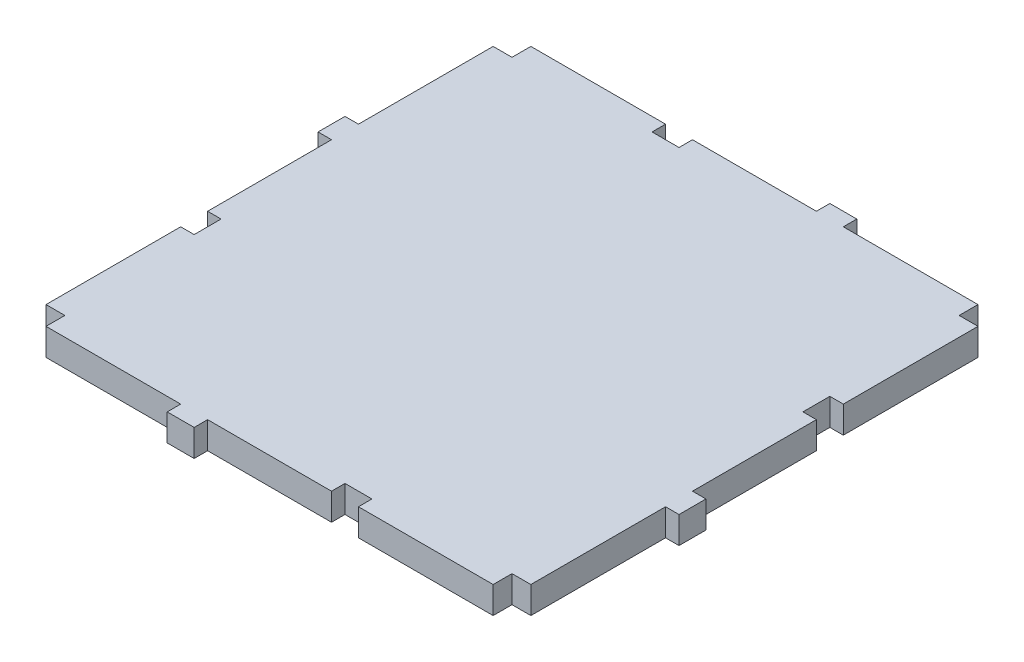
SolidWorks part; units mm, degrees
material "Pine"
ref_plane "Front Plane" through (0, 0, 0) normal (0, 0, 1) x (1, 0, 0)
ref_plane "Top Plane" through (0, 0, 0) normal (0, 1, 0) x (1, 0, 0)
ref_plane "Right Plane" through (0, 0, 0) normal (1, 0, 0) x (0, 0, -1)
sketch "Sketch2" plane through (0, 0, 0) normal (0, 1, 0) x (1, 0, 0)
  line L0 (-90, 180) -> (-90, 0)
  line L1 (0, 0) -> (-180, 0)
  line L2 (0, 0) -> (0, 180)
  line L3 (0, 180) -> (-180, 180)
  line L4 (-180, 0) -> (-180, 180)
  line L5 (-180, 90) -> (0, 90)
  dimension "D1" = 180
  dimension "D2" = 180
extrude "Boss-Extrude1" add sketch "Sketch2" along normal blind 10 contours L2 L3 L4 L1
sketch "Sketch9" plane through (0, 10, 0) normal (0, 1, 0) x (1, 0, 0)
  line L0 (-180, 0) -> (-180, 180) construction
  line L2 (0, 0) -> (-180, 0) construction
  line L3 (7, -7) -> (-7, -7)
  line L5 (0, 0) -> (0, 180) construction
  line L11 (7, -7) -> (7, 7)
  line L12 (7, 7) -> (-7, 7)
  line L13 (-7, -7) -> (-7, 7)
  line L14 (7, -7) -> (-7, 7) construction
  line L23 (7, 7) -> (-7, -7) construction
  line L24 (-187, 7) -> (-173, 7)
  line L25 (-187, 7) -> (-187, -7)
  line L26 (-187, -7) -> (-173, -7)
  line L35 (-173, 7) -> (-173, -7)
  line L36 (-187, 7) -> (-173, -7) construction
  line L37 (-187, -7) -> (-173, 7) construction
  line L47 (-173, 173) -> (-187, 173)
  line L48 (-173, 173) -> (-173, 187)
  line L49 (-173, 187) -> (-187, 187)
  line L50 (-187, 173) -> (-187, 187)
  line L59 (-173, 173) -> (-187, 187) construction
  line L60 (-173, 187) -> (-187, 173) construction
  line L61 (7, 173) -> (-7, 173)
  line L62 (7, 173) -> (7, 187)
  line L71 (7, 187) -> (-7, 187)
  line L73 (-7, 173) -> (-7, 187)
  line L74 (7, 173) -> (-7, 187) construction
  line L83 (7, 187) -> (-7, 173) construction
  point P0 (0, 0)
  point P7 (-180, 0)
  point P16 (-180, 180)
  point P21 (0, 180)
  dimension "D1" = 14
  dimension "D2" = 14
  dimension "D3" = 14
  dimension "D4" = 14
extrude "Cut-Extrude2" cut sketch "Sketch9" against normal blind 10
sketch "Sketch10" plane through (0, 10, 0) normal (0, 1, 0) x (1, 0, 0)
  line L0 (-180, 173) -> (-180, 7) construction
  line L1 (-90, 180) -> (-90, 0) construction
  line L2 (-7, 180) -> (-173, 180) construction
  line L3 (-7, 0) -> (-173, 0) construction
  line L4 (5, 123) -> (5, 113)
  line L5 (-185, 123) -> (-175, 123)
  line L6 (-185, 123) -> (-185, 113)
  line L7 (-185, 113) -> (-175, 113)
  line L8 (-175, 123) -> (-175, 113)
  line L9 (-185, 123) -> (-175, 113) construction
  line L10 (-185, 113) -> (-175, 123) construction
  line L11 (5, 123) -> (-5, 113) construction
  line L12 (5, 113) -> (-5, 123) construction
  line L13 (5, 123) -> (-5, 123)
  line L14 (-5, 123) -> (-5, 113)
  line L15 (5, 113) -> (-5, 113)
  line L16 (5, 67) -> (5, 57)
  line L17 (-185, 67) -> (-175, 67)
  line L18 (-185, 67) -> (-185, 57)
  line L19 (-185, 57) -> (-175, 57)
  line L20 (-175, 67) -> (-175, 57)
  line L21 (-185, 67) -> (-175, 57) construction
  line L22 (-185, 57) -> (-175, 67) construction
  line L23 (5, 67) -> (-5, 57) construction
  line L24 (5, 57) -> (-5, 67) construction
  line L25 (5, 67) -> (-5, 67)
  line L26 (-5, 67) -> (-5, 57)
  line L27 (5, 57) -> (-5, 57)
  line L28 (-57, -5) -> (-57, 5)
  line L29 (-123, -5) -> (-113, -5)
  line L30 (-123, -5) -> (-123, 5)
  line L31 (-123, 5) -> (-113, 5)
  line L32 (-113, -5) -> (-113, 5)
  line L33 (-123, -5) -> (-113, 5) construction
  line L34 (-123, 5) -> (-113, -5) construction
  line L35 (-57, -5) -> (-67, 5) construction
  line L36 (-57, 5) -> (-67, -5) construction
  line L37 (-57, -5) -> (-67, -5)
  line L38 (-67, -5) -> (-67, 5)
  line L39 (-57, 5) -> (-67, 5)
  line L40 (-67, 175) -> (-67, 185)
  line L41 (-113, 175) -> (-123, 175)
  line L42 (-113, 175) -> (-113, 185)
  line L43 (-113, 185) -> (-123, 185)
  line L44 (-123, 175) -> (-123, 185)
  line L45 (-113, 175) -> (-123, 185) construction
  line L46 (-113, 185) -> (-123, 175) construction
  line L47 (-67, 175) -> (-57, 185) construction
  line L48 (-67, 185) -> (-57, 175) construction
  line L49 (-67, 175) -> (-57, 175)
  line L50 (-57, 175) -> (-57, 185)
  line L51 (-67, 185) -> (-57, 185)
  point P4 (-180, 118)
  point P5 (-180, 62)
  point P6 (-180, 62)
  point P13 (0, 62)
  point P14 (0, 118)
  point P15 (-180, 118)
  point P24 (0, 118)
  point P33 (0, 62)
  point P34 (-118, 180)
  point P35 (-62, 180)
  point P36 (-118, 0)
  point P38 (-62, 0)
  point P39 (-118, 0)
  point P49 (-62, 0)
  point P50 (-118, 180)
  point P59 (-62, 180)
  point P60 (0, 0)
  point P61 (0, 0)
  dimension "D1" = 55
  dimension "D2" = 56
  dimension "D3" = 10
  dimension "D4" = 10
  dimension "D5" = 55
  dimension "D6" = 55
  dimension "D7" = 10
  dimension "D8" = 10
extrude "Boss-Extrude2" add sketch "Sketch10" against normal blind 10 contours L16 L25 L26 L27 | L40 L49 L50 L51 | L6 L5 L8 L7 | L30 L29 L32 L31
sketch "Sketch11" plane through (0, 10, 10) normal (0, 1, 0) x (1, 0, 0)
  line L0 (5, 77) -> (5, 67) construction
  line L1 (-90, 190) -> (-90, 10) construction
  line L2 (-57, 15) -> (-67, 5) construction
  line L3 (-67, 190) -> (-173, 190) construction
  line L9 (-7, 10) -> (-113, 10) construction
  line L11 (-180, 17) -> (-180, 123) construction
  line L12 (-173, 183) -> (-173, 190) construction
  line L17 (-185, 77) -> (-175, 77)
  line L18 (-185, 77) -> (-185, 67)
  line L19 (-185, 67) -> (-175, 67)
  line L20 (-175, 77) -> (-175, 67)
  line L21 (-185, 77) -> (-175, 67) construction
  line L22 (-185, 67) -> (-175, 77) construction
  line L23 (-57, 5) -> (-67, 15) construction
  line L24 (-67, 5) -> (-67, 15)
  line L35 (-57, 15) -> (-67, 15)
  line L36 (-57, 5) -> (-57, 15)
  line L41 (-113, 185) -> (-123, 185)
  line L42 (-113, 185) -> (-113, 195)
  line L43 (-113, 195) -> (-123, 195)
  line L44 (-123, 185) -> (-123, 195)
  line L45 (-113, 185) -> (-123, 195) construction
  line L46 (-113, 195) -> (-123, 185) construction
  line L47 (-57, 5) -> (-67, 5)
  line L48 (5, 123) -> (-5, 133) construction
  line L52 (5, 133) -> (-5, 123) construction
  line L53 (0, 77) -> (0, 183) construction
  line L54 (-5, 133) -> (-5, 123)
  line L55 (5, 123) -> (-5, 123)
  line L56 (5, 133) -> (5, 123)
  line L57 (5, 133) -> (-5, 133)
  point P0 (-90, 14.3765)
  point P2 (0, 0)
  point P4 (0, 0)
  point P5 (-180, 72)
  point P6 (-180, 72)
  point P9 (0, 0)
  point P13 (0, 0)
  point P14 (0, 0)
  point P17 (0, 0)
  point P18 (0, 0)
  point P19 (0, 0)
  point P20 (0, 0)
  point P21 (0, 0)
  point P22 (0, 0)
  point P33 (0, 0)
  point P34 (-118, 190)
  point P35 (0, 0)
  point P36 (-193.6599, 60.7126)
  point P37 (-180, 72)
  point P39 (-62, 10)
  point P40 (-62, 10)
  point P41 (0, 128)
  point P42 (0, 128)
  point P48 (-62, 10)
  point P49 (-62, 10)
  point P50 (-118, 190)
  point P60 (0, 0)
  point P61 (0, 0)
  point P71 (0, 128)
  point P72 (0, 128)
  dimension "D1" = 55
  dimension "D2" = 55
  dimension "D3" = 55
  dimension "D4" = 10
  dimension "D5" = 90
  dimension "D6" = 55
  dimension "D7" = 10
  dimension "D8" = 10
  dimension "D9" = 10
extrude "Cut-Extrude3" cut sketch "Sketch11" against normal blind 10
